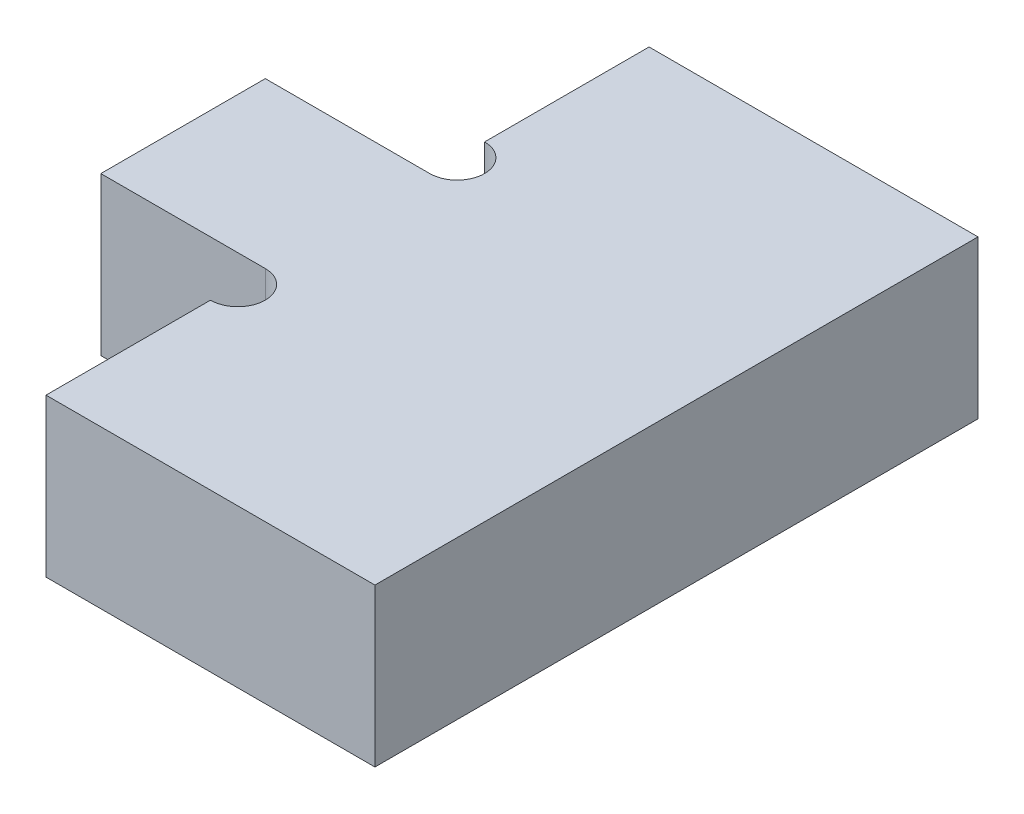
SolidWorks part; units mm, degrees
ref_plane "Front Plane" through (0, 0, 0) normal (0, 0, 1) x (1, 0, 0)
ref_plane "Top Plane" through (0, 0, 0) normal (0, 1, 0) x (1, 0, 0)
ref_plane "Right Plane" through (0, 0, 0) normal (1, 0, 0) x (0, 0, -1)
sketch "Sketch1" plane through (0, 0, 0) normal (0, 1, 0) x (1, 0, 0)
  line L0 (7.9375, 34.925) -> (7.9375, 15.875)
  line L1 (7.9375, 9.525) -> (-11.1125, 9.525)
  line L2 (-11.1125, 9.525) -> (-11.1125, -9.525)
  line L3 (-11.1125, -9.525) -> (7.9375, -9.525)
  line L4 (7.9375, -15.875) -> (7.9375, -34.925)
  line L5 (7.9375, 34.925) -> (46.0375, 34.925)
  line L6 (46.0375, 34.925) -> (46.0375, -34.925)
  line L7 (46.0375, -34.925) -> (7.9375, -34.925)
  arc A0 (7.9375, 9.525) -> (7.9375, 15.875) centre (7.9375, 12.7) ccw
  arc A1 (7.9375, -15.875) -> (7.9375, -9.525) centre (7.9375, -12.7) ccw
  dimension "D1" = 3.175
  dimension "D2" = 19.05
  dimension "D3" = 19.05
  dimension "D4" = 38.1
  dimension "D5" = 19.05
extrude "Boss-Extrude1" add sketch "Sketch1" along normal blind 18.2562
